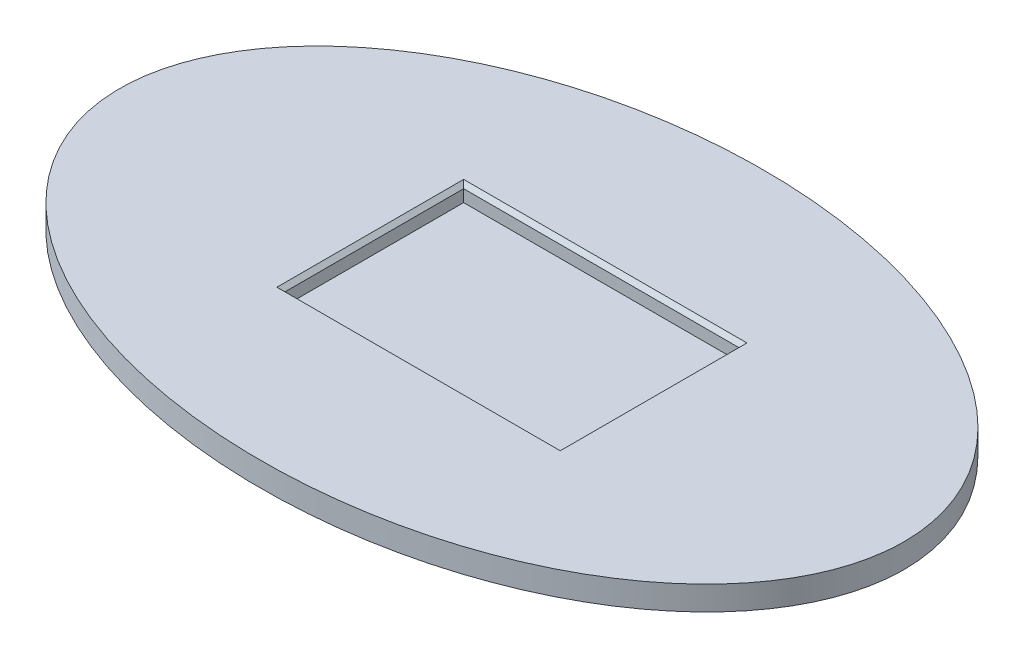
SolidWorks part; units mm, degrees
ref_plane "Front Plane" through (0, 0, 0) normal (0, 0, 1) x (1, 0, 0)
ref_plane "Top Plane" through (0, 0, 0) normal (0, 1, 0) x (1, 0, 0)
ref_plane "Right Plane" through (0, 0, 0) normal (1, 0, 0) x (0, 0, -1)
sketch "Sketch2" plane through (0, 0, 0) normal (0, 1, 0) x (1, 0, 0)
  ellipse E0 centre (0, 0) end of major axis (97.5, 0) minor radius 62.5
  dimension "D1" = 195
  dimension "D2" = 125
extrude "Boss-Extrude1" add sketch "Sketch2" along normal mid plane 6
sketch "Sketch3" plane through (0, 3, 0) normal (0, 1, 0) x (1, 0, 0)
  line L1 (-34.2, 22.2) -> (34.2, 22.2)
  line L2 (-34.2, 22.2) -> (-34.2, -22.2)
  line L3 (-34.2, -22.2) -> (34.2, -22.2)
  line L4 (34.2, 22.2) -> (34.2, -22.2)
  line L5 (-34.2, 22.2) -> (34.2, -22.2) construction
  line L6 (-34.2, -22.2) -> (34.2, 22.2) construction
  point P0 (0, 0)
  dimension "D1" = 68.4
  dimension "D2" = 44.4
extrude "Cut-Extrude1" cut sketch "Sketch3" against normal blind 4
chamfer "Chamfer2" distance 1 angle 45 4 edges at (34.2, 3, 0) (0, 3, -22.2) (-34.2, 3, 0) (0, 3, 22.2)
